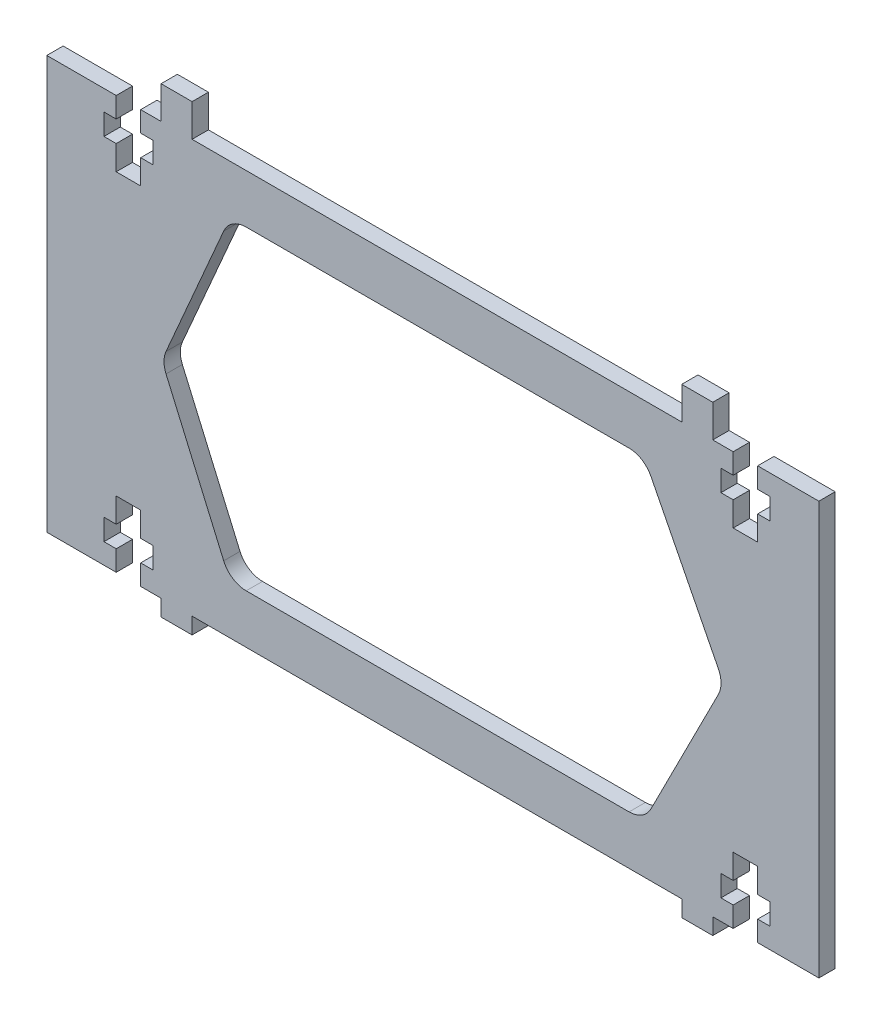
SolidWorks part; units mm, degrees
ref_plane "前视基准面" through (0, 0, 0) normal (0, 0, 1) x (1, 0, 0)
ref_plane "上视基准面" through (0, 0, 0) normal (0, 1, 0) x (1, 0, 0)
ref_plane "右视基准面" through (0, 0, 0) normal (1, 0, 0) x (0, 0, -1)
sketch "草图1" plane through (0, 0, 0) normal (0, 0, 1) x (1, 0, 0)
  line L0 (-63.2786, -35.4543) -> (-63.2786, -33.4543)
  line L1 (-63.2786, -33.4543) -> (-65.7786, -33.4543)
  line L2 (4.3214, 21.1457) -> (0.5214, 21.1457)
  line L3 (4.3214, 17.1457) -> (6.8214, 17.1457)
  line L4 (9.8214, 17.1457) -> (17.3214, 17.1457)
  line L5 (4.3214, 21.1457) -> (4.3214, 17.1457)
  line L6 (-65.7786, -30.9543) -> (-65.7786, -33.4543)
  line L7 (5.3214, 14.6457) -> (5.3214, 12.0457)
  line L8 (5.3214, 12.0457) -> (6.8214, 12.0457)
  line L9 (6.8214, 12.0457) -> (6.8214, 9.0457)
  line L10 (9.8214, 12.0457) -> (9.8214, 9.0457)
  line L11 (11.3214, 12.0457) -> (9.8214, 12.0457)
  line L12 (11.3214, 14.6457) -> (11.3214, 12.0457)
  line L13 (6.8214, 14.6457) -> (5.3214, 14.6457)
  line L14 (6.8214, 9.0457) -> (9.8214, 9.0457)
  line L15 (9.8214, 14.6457) -> (11.3214, 14.6457)
  line L16 (6.8214, 14.6457) -> (6.8214, 17.1457)
  line L17 (9.8214, 14.6457) -> (9.8214, 17.1457)
  line L18 (0.5214, -35.4543) -> (0.5214, -33.4543)
  line L19 (17.3214, -33.4543) -> (9.8214, -33.4543)
  line L20 (6.8214, -30.9543) -> (6.8214, -33.4543)
  line L21 (9.8214, -33.4543) -> (9.8214, -30.9543)
  line L22 (6.8214, -25.3543) -> (9.8214, -25.3543)
  line L23 (6.8214, -30.9543) -> (5.3214, -30.9543)
  line L24 (9.8214, -30.9543) -> (11.3214, -30.9543)
  line L25 (11.3214, -30.9543) -> (11.3214, -28.3543)
  line L26 (9.8214, -28.3543) -> (9.8214, -25.3543)
  line L27 (6.8214, -28.3543) -> (6.8214, -25.3543)
  line L28 (5.3214, -28.3543) -> (6.8214, -28.3543)
  line L29 (5.3214, -30.9543) -> (5.3214, -28.3543)
  line L30 (4.3214, -35.4543) -> (4.3214, -33.4543)
  line L31 (11.3214, -28.3543) -> (9.8214, -28.3543)
  line L32 (4.3214, -33.4543) -> (6.8214, -33.4543)
  line L33 (0.5214, 21.1457) -> (0.5214, 17.1457)
  line L34 (4.3214, -35.4543) -> (0.5214, -35.4543)
  line L35 (-77.2786, -33.4543) -> (-77.2786, 17.1457)
  line L36 (-59.4786, 17.1457) -> (0.5214, 17.1457)
  line L37 (-63.2786, -35.4543) -> (-59.4786, -35.4543)
  line L38 (17.3214, -33.4543) -> (17.3214, 17.1457)
  line L39 (-68.7786, -33.4543) -> (-77.2786, -33.4543)
  line L40 (6.8214, -25.3543) -> (6.8214, 9.0457) construction
  line L41 (-59.4786, -33.4543) -> (0.5214, -33.4543)
  line L42 (-64.2786, -30.9543) -> (-64.2786, -28.3543)
  line L43 (-64.2786, -28.3543) -> (-65.7786, -28.3543)
  line L44 (-65.7786, -28.3543) -> (-65.7786, -25.3543)
  line L45 (-68.7786, -28.3543) -> (-68.7786, -25.3543)
  line L46 (-70.2786, -28.3543) -> (-68.7786, -28.3543)
  line L47 (-70.2786, -30.9543) -> (-70.2786, -28.3543)
  line L48 (-65.7786, -30.9543) -> (-64.2786, -30.9543)
  line L49 (-65.7786, -25.3543) -> (-68.7786, -25.3543)
  line L50 (-68.7786, -30.9543) -> (-70.2786, -30.9543)
  line L51 (-3.4786, 12.1457) -> (-55.4786, 12.1457) construction
  line L52 (-68.7786, -30.9543) -> (-68.7786, -33.4543)
  line L53 (-59.4786, -35.4543) -> (-59.4786, -33.4543)
  line L54 (-59.4786, 21.1457) -> (-59.4786, 17.1457)
  line L55 (-68.7786, 14.6457) -> (-68.7786, 17.1457)
  line L56 (-65.7786, 14.6457) -> (-65.7786, 17.1457)
  line L57 (-68.7786, 14.6457) -> (-70.2786, 14.6457)
  line L58 (-65.7786, 9.0457) -> (-68.7786, 9.0457)
  line L59 (-65.7786, 14.6457) -> (-64.2786, 14.6457)
  line L60 (-70.2786, 14.6457) -> (-70.2786, 12.0457)
  line L61 (-70.2786, 12.0457) -> (-68.7786, 12.0457)
  line L62 (-68.7786, 12.0457) -> (-68.7786, 9.0457)
  line L63 (-65.7786, 12.0457) -> (-65.7786, 9.0457)
  line L64 (-64.2786, 12.0457) -> (-65.7786, 12.0457)
  line L65 (-64.2786, 14.6457) -> (-64.2786, 12.0457)
  line L66 (-59.4786, 17.1457) -> (0.5214, 17.1457)
  line L67 (-63.2786, 21.1457) -> (-63.2786, 17.1457)
  line L68 (-68.7786, 17.1457) -> (-77.2786, 17.1457)
  line L69 (-63.2786, 17.1457) -> (-65.7786, 17.1457)
  line L70 (-63.2786, 21.1457) -> (-59.4786, 21.1457)
  line L71 (-3.4786, 12.1457) -> (-3.4786, -28.4543) construction
  line L72 (-3.4786, -28.4543) -> (-55.4786, -28.4543) construction
  line L73 (-55.4786, 12.1457) -> (-55.4786, -28.4543) construction
  line L74 (-3.4786, -28.4543) -> (6.8214, -8.1543) construction
  line L75 (6.8214, -8.1543) -> (-3.4786, 12.1457) construction
  line L76 (-64.2786, 12.0457) -> (-64.2786, -28.3543) construction
  line L77 (-64.2786, -8.1543) -> (-55.4786, 12.1457) construction
  line L78 (-55.4786, -28.4543) -> (-64.2786, -8.1543) construction
  line L79 (-5.9344, 11.1457) -> (-52.8529, 11.1457)
  line L80 (-62.6714, -6.9611) -> (-55.6054, 9.3389)
  line L81 (-55.6054, -25.6475) -> (-62.6714, -9.3475)
  line L82 (-5.9344, -27.4543) -> (-52.8529, -27.4543)
  line L83 (-3.2591, -25.8117) -> (5.0113, -9.5117)
  line L84 (5.0113, -6.7969) -> (-3.2591, 9.5031)
  line L85 (-4.0925, 11.1457) -> (-54.8222, 11.1457) construction
  line L86 (-63.1887, -8.1543) -> (-54.8222, 11.1457) construction
  line L87 (-54.8222, -27.4543) -> (-63.1887, -8.1543) construction
  line L88 (-4.0925, -27.4543) -> (-54.8222, -27.4543) construction
  line L89 (-4.0925, -27.4543) -> (5.7001, -8.1543) construction
  line L90 (5.7001, -8.1543) -> (-4.0925, 11.1457) construction
  arc A0 (-52.8529, 11.1457) -> (-55.6054, 9.3389) centre (-52.8529, 8.1457) ccw
  arc A1 (-62.6714, -6.9611) -> (-62.6714, -9.3475) centre (-59.9189, -8.1543) ccw
  arc A2 (-55.6054, -25.6475) -> (-52.8529, -27.4543) centre (-52.8529, -24.4543) ccw
  arc A3 (-5.9344, -27.4543) -> (-3.2591, -25.8117) centre (-5.9344, -24.4543) ccw
  arc A4 (5.0113, -9.5117) -> (5.0113, -6.7969) centre (2.336, -8.1543) ccw
  arc A5 (-3.2591, 9.5031) -> (-5.9344, 11.1457) centre (-5.9344, 8.1457) ccw
  point P1 (6.8214, 15.8957)
  dimension "D35" = 3
  dimension "D2" = 7.5
  dimension "D3" = 3
  dimension "D4" = 2.5
  dimension "D5" = 1.5
  dimension "D6" = 2.6
  dimension "D7" = 1.5
  dimension "D8" = 3
  dimension "D9" = 3
  dimension "D10" = 3
  dimension "D11" = 2.6
  dimension "D12" = 1.5
  dimension "D13" = 2.5
  dimension "D14" = 3.8
  dimension "D15" = 4
  dimension "D16" = 8.5
  dimension "D17" = 5
  dimension "D18" = 2.5
  dimension "D19" = 1.5
  dimension "D20" = 2.6
  dimension "D21" = 1.5
  dimension "D22" = 3
  dimension "D23" = 3
  dimension "D24" = 3
  dimension "D25" = 2.6
  dimension "D26" = 1.5
  dimension "D27" = 5
  dimension "D28" = 3.8
  dimension "D29" = 2
  dimension "D30" = 60
  dimension "D31" = 50.6
  dimension "D32" = 4
  dimension "D33" = 4
  dimension "D34" = 1
  dimension "D36" = 3
extrude "凸台-拉伸1" add sketch "草图1" along normal blind 2
sketch "草图3" plane through (0, -33.4543, 0) normal (0, -1, 0) x (1, 0, 0)
  line L0 (-65.7786, 1) -> (-68.7786, 1) construction
  line L1 (-65.7786, 2) -> (-65.7786, 0) construction
  line L2 (-68.7786, 2) -> (-68.7786, 0) construction
  circle A0 centre (-67.2786, 1) radius 1.5
